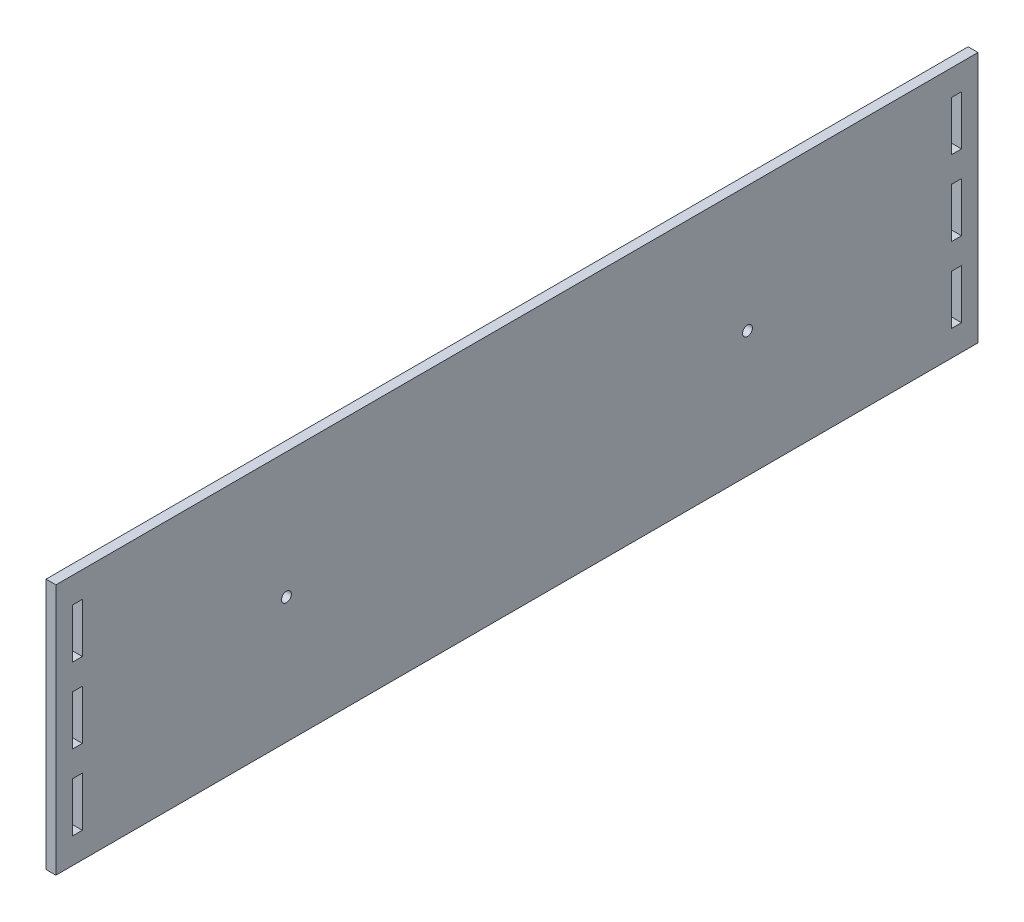
SolidWorks part; units mm, degrees
material "ENPH 253 Hardboard"
ref_plane "Front Plane" through (0, 0, 0) normal (0, 0, 1) x (1, 0, 0)
ref_plane "Top Plane" through (0, 0, 0) normal (0, 1, 0) x (1, 0, 0)
ref_plane "Right Plane" through (0, 0, 0) normal (1, 0, 0) x (0, 0, -1)
sketch "Sketch1" plane through (0, 0, 0) normal (1, 0, 0) x (0, 0, -1)
  line L1 (-139.7, 38.1) -> (139.7, 38.1)
  line L2 (-139.7, 38.1) -> (-139.7, -38.1)
  line L3 (-139.7, -38.1) -> (139.7, -38.1)
  line L4 (139.7, 38.1) -> (139.7, -38.1)
  line L5 (-139.7, 38.1) -> (139.7, -38.1) construction
  line L6 (-139.7, -38.1) -> (139.7, 38.1) construction
  point P0 (0, 0)
  dimension "D1" = 279.4
  dimension "D2" = 76.2
extrude "Boss-Extrude1" add sketch "Sketch1" against normal blind 3 contours L2 L3 L4 L1
sketch "Sketch3" plane through (-3, 0, 0) normal (-1, 0, 0) x (0, 0, 1)
  line L0 (-139.7, 38.1) -> (-139.7, -38.1) construction
  line L1 (139.7, 38.1) -> (139.7, -38.1) construction
  line L2 (139.7, 38.1) -> (-139.7, 38.1) construction
  line L3 (134.7, 30.3) -> (131.7, 30.3)
  line L4 (134.7, 30.3) -> (134.7, 15.3)
  line L5 (134.7, 15.3) -> (131.7, 15.3)
  line L6 (131.7, 30.3) -> (131.7, 15.3)
  line L7 (139.7, 38.1) -> (139.7, -38.1) construction
  circle A0 centre (69.85, 0) radius 50.8 construction
  circle A1 centre (-69.85, 0) radius 50.8 construction
  dimension "D1" = 101.6
  dimension "D2" = 101.6
  dimension "D3" = 69.85
  dimension "D4" = 69.85
  dimension "D5" = 15
  dimension "D6" = 7.8
  dimension "D7" = 5
  dimension "D8" = 3
extrude "Cut-Extrude1" cut sketch "Sketch3" against normal through all
pattern_linear "LPattern1" count 3 spacing 22.8 along (0, -1, 0) of "Cut-Extrude1"
mirror "Mirror1" about plane through (0, 0, 0) normal (0, 0, 1) of "LPattern1", "Cut-Extrude1"
hole_wizard "Ø3.0mm Clearance Dowel Hole1" positions "Sketch4" profile "Sketch5" hole size "Ø3.0" standard "ANSI Metric" end condition through all
sketch "Sketch4" plane through (-3, 0, 0) normal (-1, 0, 0) x (0, 0, 1)
  point P0 (-69.85, 0)
  point P3 (69.85, 0)
sketch "Sketch5" plane through (-3, 0, -69.85) normal (0, 1, 0) x (0, 0, 1)
  line L0 (0, 0) -> (0, 3)
  line L1 (0, 3) -> (1.5, 3)
  line L2 (1.5, 3) -> (1.5, 0)
  line L5 (1.5, 0) -> (0, 0)
  line L11 (0, -6.35) -> (0, 107.95) construction
  dimension "Thru Hole Dia." = 3
  dimension "Thru Hole Depth" = 3
equation "\"D4@Sketch3\"=\"D3@Sketch3\""
